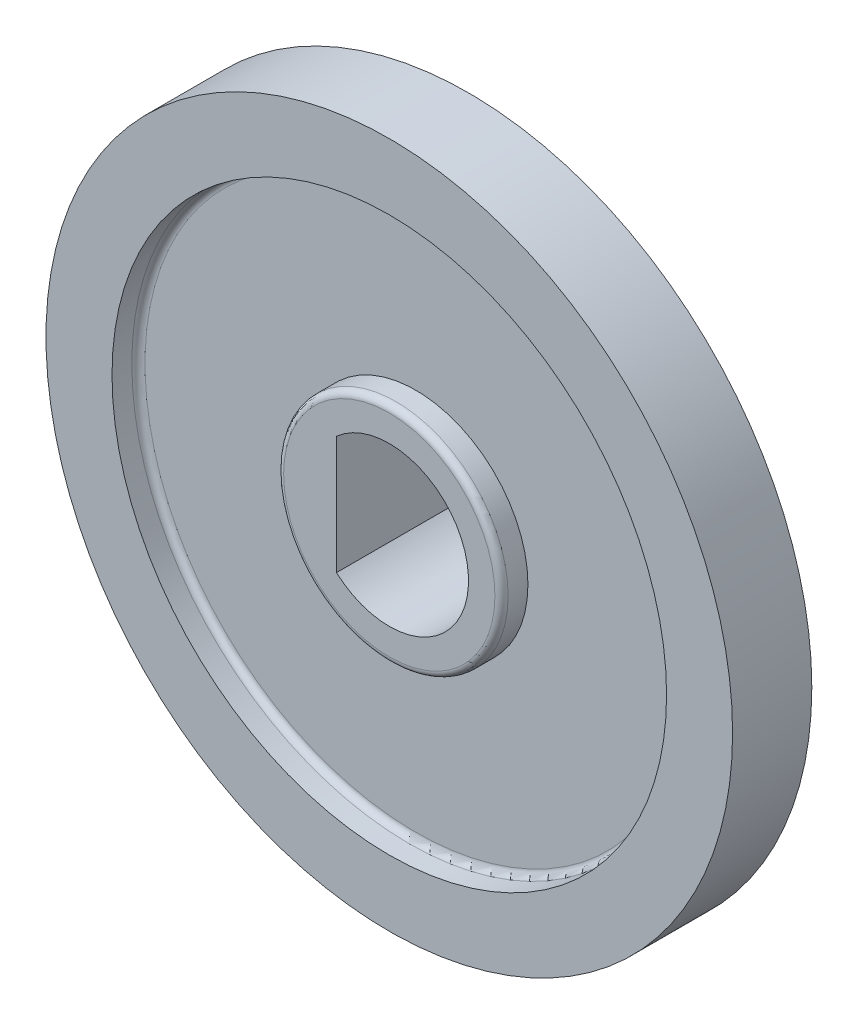
SolidWorks part; units mm, degrees
ref_plane "Plan de face" through (0, 0, 0) normal (0, 0, 1) x (1, 0, 0)
ref_plane "Plan de dessus" through (0, 0, 0) normal (0, 1, 0) x (1, 0, 0)
ref_plane "Plan de droite" through (0, 0, 0) normal (1, 0, 0) x (0, 0, -1)
sketch "Esquisse1" plane through (0, 0, 0) normal (0, 0, 1) x (1, 0, 0)
  line L0 (-2, 2.2361) -> (-2, -2.2361)
  arc A0 (12.9936, 0.4084) -> (12.9756, 0.7954) centre (0, 0) ccw
  arc A1 (12.8399, 2.0337) -> (12.7736, 2.4154) centre (0, 0) ccw
  arc A2 (12.4838, 3.6269) -> (12.3702, 3.9974) centre (0, 0) ccw
  arc A3 (11.9308, 5.1629) -> (11.7716, 5.5162) centre (0, 0) ccw
  arc A4 (11.1896, 6.6175) -> (10.9874, 6.9481) centre (0, 0) ccw
  arc A5 (10.272, 7.9678) -> (10.03, 8.2704) centre (0, 0) ccw
  arc A6 (9.1924, 9.1924) -> (8.9143, 9.4623) centre (0, 0) ccw
  arc A7 (7.9678, 10.272) -> (7.6581, 10.5049) centre (0, 0) ccw
  arc A8 (6.6175, 11.1897) -> (6.2811, 11.3819) centre (0, 0) ccw
  arc A9 (5.1629, 11.9308) -> (4.805, 12.0794) centre (0, 0) ccw
  arc A10 (3.6269, 12.4838) -> (3.2532, 12.5864) centre (0, 0) ccw
  arc A11 (2.0336, 12.84) -> (1.6501, 12.8949) centre (0, 0) ccw
  arc A12 (0.4083, 12.9936) -> (0.0209, 13) centre (0, 0) ccw
  arc A13 (-1.2234, 12.9423) -> (-1.6086, 12.9001) centre (0, 0) ccw
  arc A14 (-2.8359, 12.6869) -> (-3.2127, 12.5968) centre (0, 0) ccw
  arc A15 (-4.4036, 12.2314) -> (-4.7662, 12.0948) centre (0, 0) ccw
  arc A16 (-5.9019, 11.5831) -> (-6.2445, 11.402) centre (0, 0) ccw
  arc A17 (-7.3071, 10.752) -> (-7.6243, 10.5295) centre (0, 0) ccw
  arc A18 (-8.5971, 9.7514) -> (-8.8839, 9.4909) centre (0, 0) ccw
  arc A19 (-9.7515, 8.597) -> (-10.0033, 8.3026) centre (0, 0) ccw
  arc A20 (-10.7521, 7.3071) -> (-10.9651, 6.9834) centre (0, 0) ccw
  arc A21 (-11.5831, 5.9019) -> (-11.7538, 5.554) centre (0, 0) ccw
  arc A22 (-12.2315, 4.4036) -> (-12.3573, 4.0371) centre (0, 0) ccw
  arc A23 (-12.6869, 2.8358) -> (-12.7658, 2.4565) centre (0, 0) ccw
  arc A24 (-12.9423, 1.2234) -> (-12.973, 0.8371) centre (0, 0) ccw
  arc A25 (-12.9936, -0.4084) -> (-12.9756, -0.7954) centre (0, 0) ccw
  arc A26 (-12.8399, -2.0337) -> (-12.7736, -2.4154) centre (0, 0) ccw
  arc A27 (-12.4838, -3.6269) -> (-12.3702, -3.9974) centre (0, 0) ccw
  arc A28 (-11.9308, -5.1629) -> (-11.7716, -5.5162) centre (0, 0) ccw
  arc A29 (-11.1896, -6.6175) -> (-10.9874, -6.9481) centre (0, 0) ccw
  arc A30 (-10.272, -7.9678) -> (-10.03, -8.2704) centre (0, 0) ccw
  arc A31 (-9.1924, -9.1924) -> (-8.9143, -9.4623) centre (0, 0) ccw
  arc A32 (-7.9678, -10.272) -> (-7.6581, -10.5049) centre (0, 0) ccw
  arc A33 (-6.6175, -11.1897) -> (-6.2811, -11.3819) centre (0, 0) ccw
  arc A34 (-5.1629, -11.9308) -> (-4.805, -12.0794) centre (0, 0) ccw
  arc A35 (-3.6269, -12.4838) -> (-3.2532, -12.5864) centre (0, 0) ccw
  arc A36 (-2.0336, -12.84) -> (-1.6501, -12.8949) centre (0, 0) ccw
  arc A37 (-0.4083, -12.9936) -> (-0.0209, -13) centre (0, 0) ccw
  arc A38 (1.2234, -12.9423) -> (1.6086, -12.9001) centre (0, 0) ccw
  arc A39 (2.8359, -12.6869) -> (3.2127, -12.5968) centre (0, 0) ccw
  arc A40 (4.4036, -12.2314) -> (4.7662, -12.0948) centre (0, 0) ccw
  arc A41 (5.9019, -11.5831) -> (6.2445, -11.402) centre (0, 0) ccw
  arc A42 (7.3071, -10.752) -> (7.6243, -10.5295) centre (0, 0) ccw
  arc A43 (8.5971, -9.7514) -> (8.8839, -9.4909) centre (0, 0) ccw
  arc A44 (9.7515, -8.597) -> (10.0033, -8.3026) centre (0, 0) ccw
  arc A45 (10.7521, -7.3071) -> (10.9651, -6.9834) centre (0, 0) ccw
  arc A46 (11.5831, -5.9019) -> (11.7538, -5.554) centre (0, 0) ccw
  arc A47 (12.2315, -4.4036) -> (12.3573, -4.0371) centre (0, 0) ccw
  arc A48 (12.6869, -2.8358) -> (12.7658, -2.4565) centre (0, 0) ccw
  arc A49 (12.9423, -1.2234) -> (12.973, -0.8371) centre (0, 0) ccw
  arc A50 (11.8681, -0.4041) -> (11.875, 0.012) centre (0, 0) ccw
  arc A51 (11.8252, 1.0866) -> (11.7798, 1.5003) centre (0, 0) ccw
  arc A52 (11.5958, 2.5601) -> (11.4989, 2.9648) centre (0, 0) ccw
  arc A53 (11.1835, 3.9932) -> (11.0367, 4.3827) centre (0, 0) ccw
  arc A54 (10.5948, 5.3634) -> (10.4003, 5.7314) centre (0, 0) ccw
  arc A55 (9.839, 6.649) -> (9.6, 6.9897) centre (0, 0) ccw
  arc A56 (8.9281, 7.8297) -> (8.6483, 8.1378) centre (0, 0) ccw
  arc A57 (7.8764, 8.887) -> (7.5601, 9.1575) centre (0, 0) ccw
  arc A58 (6.7004, 9.8041) -> (6.3528, 10.0328) centre (0, 0) ccw
  arc A59 (5.4188, 10.5666) -> (5.0452, 10.7499) centre (0, 0) ccw
  arc A60 (4.0518, 11.1624) -> (3.6581, 11.2975) centre (0, 0) ccw
  arc A61 (2.6208, 11.5822) -> (2.2133, 11.6669) centre (0, 0) ccw
  arc A62 (1.1485, 11.8193) -> (0.7336, 11.8523) centre (0, 0) ccw
  arc A63 (-0.3419, 11.8701) -> (-0.7576, 11.8508) centre (0, 0) ccw
  arc A64 (-1.8269, 11.7336) -> (-2.237, 11.6624) centre (0, 0) ccw
  arc A65 (-3.2831, 11.4121) -> (-3.681, 11.2901) centre (0, 0) ccw
  arc A66 (-4.6876, 10.9106) -> (-5.067, 10.7397) centre (0, 0) ccw
  arc A67 (-6.0181, 10.2371) -> (-6.3731, 10.0199) centre (0, 0) ccw
  arc A68 (-7.2537, 9.4021) -> (-7.5787, 9.1422) centre (0, 0) ccw
  arc A69 (-8.3749, 8.4189) -> (-8.6647, 8.1202) centre (0, 0) ccw
  arc A70 (-9.364, 7.3028) -> (-9.6141, 6.9702) centre (0, 0) ccw
  arc A71 (-10.2054, 6.0716) -> (-10.4119, 5.7103) centre (0, 0) ccw
  arc A72 (-10.886, 4.7447) -> (-11.0455, 4.3603) centre (0, 0) ccw
  arc A73 (-11.3948, 3.3429) -> (-11.5049, 2.9415) centre (0, 0) ccw
  arc A74 (-11.7239, 1.8884) -> (-11.7829, 1.4764) centre (0, 0) ccw
  arc A75 (-11.8681, 0.4041) -> (-11.875, -0.012) centre (0, 0) ccw
  arc A76 (-11.8252, -1.0866) -> (-11.7798, -1.5003) centre (0, 0) ccw
  arc A77 (-11.5958, -2.5601) -> (-11.4989, -2.9648) centre (0, 0) ccw
  arc A78 (-11.1835, -3.9932) -> (-11.0367, -4.3827) centre (0, 0) ccw
  arc A79 (-10.5948, -5.3634) -> (-10.4003, -5.7314) centre (0, 0) ccw
  arc A80 (-9.839, -6.649) -> (-9.6, -6.9897) centre (0, 0) ccw
  arc A81 (-8.9281, -7.8297) -> (-8.6483, -8.1378) centre (0, 0) ccw
  arc A82 (-7.8764, -8.887) -> (-7.5601, -9.1575) centre (0, 0) ccw
  arc A83 (-6.7004, -9.8041) -> (-6.3528, -10.0328) centre (0, 0) ccw
  arc A84 (-5.4188, -10.5666) -> (-5.0452, -10.7499) centre (0, 0) ccw
  arc A85 (-4.0518, -11.1624) -> (-3.6581, -11.2975) centre (0, 0) ccw
  arc A86 (-2.6208, -11.5822) -> (-2.2133, -11.6669) centre (0, 0) ccw
  arc A87 (-1.1485, -11.8193) -> (-0.7336, -11.8523) centre (0, 0) ccw
  arc A88 (0.3419, -11.8701) -> (0.7576, -11.8508) centre (0, 0) ccw
  arc A89 (1.8269, -11.7336) -> (2.237, -11.6624) centre (0, 0) ccw
  arc A90 (3.2831, -11.4121) -> (3.681, -11.2901) centre (0, 0) ccw
  arc A91 (4.6876, -10.9106) -> (5.067, -10.7397) centre (0, 0) ccw
  arc A92 (6.0181, -10.2371) -> (6.3731, -10.0199) centre (0, 0) ccw
  arc A93 (7.2537, -9.4021) -> (7.5787, -9.1422) centre (0, 0) ccw
  arc A94 (8.3749, -8.4189) -> (8.6647, -8.1202) centre (0, 0) ccw
  arc A95 (9.364, -7.3028) -> (9.6141, -6.9702) centre (0, 0) ccw
  arc A96 (10.2054, -6.0716) -> (10.4119, -5.7103) centre (0, 0) ccw
  arc A97 (10.886, -4.7447) -> (11.0455, -4.3603) centre (0, 0) ccw
  arc A98 (11.3948, -3.3429) -> (11.5049, -2.9415) centre (0, 0) ccw
  arc A99 (11.7239, -1.8884) -> (11.7829, -1.4764) centre (0, 0) ccw
  arc A100 (-2, -2.2361) -> (-2, 2.2361) centre (0, 0) ccw
  spline S0 degree 3 poles (11.875, 0.012) (11.8924, 0.0149) (12.1056, 0.0543) (12.4729, 0.1636) (12.819, 0.3195) (12.9805, 0.4016) (12.9936, 0.4084) knots 0.129628 0.129628 0.129628 0.129628 0.182246 0.777177 1.275527 1.319645 1.319645 1.319645 1.319645
  spline S1 degree 3 poles (11.8252, 1.0866) (11.8427, 1.0853) (12.0587, 1.0658) (12.4346, 0.991) (12.7936, 0.8677) (12.962, 0.8009) (12.9756, 0.7954) knots 0.129628 0.129628 0.129628 0.129628 0.182246 0.777177 1.275527 1.319645 1.319645 1.319645 1.319645
  spline S2 degree 3 poles (11.7798, 1.5003) (11.7967, 1.5053) (12.0034, 1.5711) (12.3541, 1.7256) (12.6778, 1.9236) (12.8278, 2.0253) (12.8399, 2.0337) knots 0.129628 0.129628 0.129628 0.129628 0.182246 0.777177 1.275527 1.319645 1.319645 1.319645 1.319645
  spline S3 degree 3 poles (11.5958, 2.5601) (11.6133, 2.5611) (11.8301, 2.5688) (12.2123, 2.5416) (12.5839, 2.4644) (12.7594, 2.4192) (12.7736, 2.4154) knots 0.129628 0.129628 0.129628 0.129628 0.182246 0.777177 1.275527 1.319645 1.319645 1.319645 1.319645
  spline S4 degree 3 poles (11.4989, 2.9648) (11.515, 2.9719) (11.7118, 3.0631) (12.0404, 3.2603) (12.3368, 3.4974) (12.4728, 3.6171) (12.4838, 3.6269) knots 0.129628 0.129628 0.129628 0.129628 0.182246 0.777177 1.275527 1.319645 1.319645 1.319645 1.319645
  spline S5 degree 3 poles (11.1835, 3.9932) (11.2008, 3.9964) (11.4148, 4.0312) (11.7975, 4.0522) (12.1758, 4.0221) (12.3556, 3.9993) (12.3702, 3.9974) knots 0.129628 0.129628 0.129628 0.129628 0.182246 0.777177 1.275527 1.319645 1.319645 1.319645 1.319645
  spline S6 degree 3 poles (11.0367, 4.3827) (11.0518, 4.3917) (11.2355, 4.5069) (11.5368, 4.7437) (11.8012, 5.0161) (11.9211, 5.1519) (11.9308, 5.1629) knots 0.129628 0.129628 0.129628 0.129628 0.182246 0.777177 1.275527 1.319645 1.319645 1.319645 1.319645
  spline S7 degree 3 poles (10.5948, 5.3634) (10.6116, 5.3687) (10.8196, 5.4301) (11.1966, 5.4989) (11.5757, 5.5164) (11.7569, 5.5163) (11.7716, 5.5162) knots 0.129628 0.129628 0.129628 0.129628 0.182246 0.777177 1.275527 1.319645 1.319645 1.319645 1.319645
  spline S8 degree 3 poles (10.4003, 5.7314) (10.4142, 5.7422) (10.5821, 5.8795) (10.8513, 6.1522) (11.0794, 6.4556) (11.1814, 6.6053) (11.1896, 6.6175) knots 0.129628 0.129628 0.129628 0.129628 0.182246 0.777177 1.275527 1.319645 1.319645 1.319645 1.319645
  spline S9 degree 3 poles (9.839, 6.649) (9.855, 6.6564) (10.0537, 6.7433) (10.4191, 6.8588) (10.793, 6.9238) (10.9728, 6.9463) (10.9874, 6.9481) knots 0.129628 0.129628 0.129628 0.129628 0.182246 0.777177 1.275527 1.319645 1.319645 1.319645 1.319645
  spline S10 degree 3 poles (9.6, 6.9897) (9.6124, 7.0022) (9.7617, 7.1594) (9.9947, 7.4638) (10.183, 7.7933) (10.2654, 7.9547) (10.272, 7.9678) knots 0.129628 0.129628 0.129628 0.129628 0.182246 0.777177 1.275527 1.319645 1.319645 1.319645 1.319645
  spline S11 degree 3 poles (8.9281, 7.8297) (8.943, 7.839) (9.1293, 7.9502) (9.4773, 8.1106) (9.8402, 8.2219) (10.0157, 8.2668) (10.03, 8.2704) knots 0.129628 0.129628 0.129628 0.129628 0.182246 0.777177 1.275527 1.319645 1.319645 1.319645 1.319645
  spline S12 degree 3 poles (8.6483, 8.1378) (8.659, 8.1517) (8.7874, 8.3265) (8.9804, 8.6576) (9.1259, 9.0081) (9.1874, 9.1785) (9.1924, 9.1924) knots 0.129628 0.129628 0.129628 0.129628 0.182246 0.777177 1.275527 1.319645 1.319645 1.319645 1.319645
  spline S13 degree 3 poles (7.8764, 8.887) (7.89, 8.8981) (8.0608, 9.0317) (8.386, 9.2344) (8.7321, 9.3904) (8.9006, 9.4569) (8.9143, 9.4623) knots 0.129628 0.129628 0.129628 0.129628 0.182246 0.777177 1.275527 1.319645 1.319645 1.319645 1.319645
  spline S14 degree 3 poles (7.5601, 9.1575) (7.569, 9.1727) (7.6746, 9.3622) (7.8245, 9.7148) (7.9249, 10.0809) (7.9646, 10.2576) (7.9678, 10.272) knots 0.129628 0.129628 0.129628 0.129628 0.182246 0.777177 1.275527 1.319645 1.319645 1.319645 1.319645
  spline S15 degree 3 poles (6.7004, 9.8041) (6.7126, 9.8168) (6.8653, 9.9708) (7.1625, 10.2127) (7.4863, 10.4107) (7.6451, 10.4979) (7.6581, 10.5049) knots 0.129628 0.129628 0.129628 0.129628 0.182246 0.777177 1.275527 1.319645 1.319645 1.319645 1.319645
  spline S16 degree 3 poles (6.3528, 10.0328) (6.3597, 10.049) (6.4407, 10.2502) (6.5452, 10.6189) (6.599, 10.9946) (6.6162, 11.175) (6.6175, 11.1897) knots 0.129628 0.129628 0.129628 0.129628 0.182246 0.777177 1.275527 1.319645 1.319645 1.319645 1.319645
  spline S17 degree 3 poles (5.4188, 10.5666) (5.4293, 10.5807) (5.5615, 10.7526) (5.8261, 11.0299) (6.1225, 11.2669) (6.2691, 11.3733) (6.2811, 11.3819) knots 0.129628 0.129628 0.129628 0.129628 0.182246 0.777177 1.275527 1.319645 1.319645 1.319645 1.319645
  spline S18 degree 3 poles (5.0452, 10.7499) (5.0501, 10.7669) (5.1052, 10.9766) (5.1627, 11.3555) (5.169, 11.735) (5.1634, 11.9161) (5.1629, 11.9308) knots 0.129628 0.129628 0.129628 0.129628 0.182246 0.777177 1.275527 1.319645 1.319645 1.319645 1.319645
  spline S19 degree 3 poles (4.0518, 11.1624) (4.0604, 11.1777) (4.17, 11.3649) (4.3977, 11.6731) (4.6621, 11.9454) (4.7942, 12.0694) (4.805, 12.0794) knots 0.129628 0.129628 0.129628 0.129628 0.182246 0.777177 1.275527 1.319645 1.319645 1.319645 1.319645
  spline S20 degree 3 poles (3.6581, 11.2975) (3.6608, 11.3149) (3.6892, 11.5299) (3.6988, 11.913) (3.6574, 12.2903) (3.6292, 12.4693) (3.6269, 12.4838) knots 0.129628 0.129628 0.129628 0.129628 0.182246 0.777177 1.275527 1.319645 1.319645 1.319645 1.319645
  spline S21 degree 3 poles (2.6208, 11.5822) (2.6274, 11.5985) (2.7127, 11.7979) (2.9, 12.1322) (3.1282, 12.4355) (3.2437, 12.5751) (3.2532, 12.5864) knots 0.129628 0.129628 0.129628 0.129628 0.182246 0.777177 1.275527 1.319645 1.319645 1.319645 1.319645
  spline S22 degree 3 poles (2.2133, 11.6669) (2.2138, 11.6845) (2.215, 11.9014) (2.1765, 12.2827) (2.0882, 12.6518) (2.0378, 12.8258) (2.0336, 12.84) knots 0.129628 0.129628 0.129628 0.129628 0.182246 0.777177 1.275527 1.319645 1.319645 1.319645 1.319645
  spline S23 degree 3 poles (1.1485, 11.8193) (1.153, 11.8363) (1.2126, 12.0449) (1.3566, 12.4) (1.5449, 12.7295) (1.6421, 12.8824) (1.6501, 12.8949) knots 0.129628 0.129628 0.129628 0.129628 0.182246 0.777177 1.275527 1.319645 1.319645 1.319645 1.319645
  spline S24 degree 3 poles (0.7336, 11.8523) (0.7319, 11.8698) (0.7059, 12.0851) (0.6199, 12.4586) (0.486, 12.8137) (0.4142, 12.9801) (0.4083, 12.9936) knots 0.129628 0.129628 0.129628 0.129628 0.182246 0.777177 1.275527 1.319645 1.319645 1.319645 1.319645
  spline S25 degree 3 poles (-0.3419, 11.8701) (-0.3396, 11.8875) (-0.3065, 12.1019) (-0.2082, 12.4723) (-0.0627, 12.8228) (0.0146, 12.9867) (0.0209, 13) knots 0.129628 0.129628 0.129628 0.129628 0.182246 0.777177 1.275527 1.319645 1.319645 1.319645 1.319645
  spline S26 degree 3 poles (-0.7576, 11.8508) (-0.7616, 11.868) (-0.8143, 12.0783) (-0.9465, 12.438) (-1.1238, 12.7736) (-1.2159, 12.9296) (-1.2234, 12.9423) knots 0.129628 0.129628 0.129628 0.129628 0.182246 0.777177 1.275527 1.319645 1.319645 1.319645 1.319645
  spline S27 degree 3 poles (-1.8269, 11.7336) (-1.8268, 11.7512) (-1.8209, 11.968) (-1.7698, 12.3478) (-1.6693, 12.7138) (-1.6132, 12.8861) (-1.6086, 12.9001) knots 0.129628 0.129628 0.129628 0.129628 0.182246 0.777177 1.275527 1.319645 1.319645 1.319645 1.319645
  spline S28 degree 3 poles (-2.237, 11.6624) (-2.243, 11.6789) (-2.3217, 11.881) (-2.4979, 12.2213) (-2.7159, 12.532) (-2.8268, 12.6753) (-2.8359, 12.6869) knots 0.129628 0.129628 0.129628 0.129628 0.182246 0.777177 1.275527 1.319645 1.319645 1.319645 1.319645
  spline S29 degree 3 poles (-3.2831, 11.4121) (-3.2852, 11.4296) (-3.3065, 11.6454) (-3.3034, 12.0286) (-3.2496, 12.4044) (-3.2156, 12.5823) (-3.2127, 12.5968) knots 0.129628 0.129628 0.129628 0.129628 0.182246 0.777177 1.275527 1.319645 1.319645 1.319645 1.319645
  spline S30 degree 3 poles (-3.681, 11.2901) (-3.6891, 11.3057) (-3.7925, 11.4963) (-4.0099, 11.8119) (-4.2652, 12.0928) (-4.3932, 12.2211) (-4.4036, 12.2314) knots 0.129628 0.129628 0.129628 0.129628 0.182246 0.777177 1.275527 1.319645 1.319645 1.319645 1.319645
  spline S31 degree 3 poles (-4.6876, 10.9106) (-4.6918, 10.9277) (-4.74, 11.1392) (-4.785, 11.5198) (-4.7787, 11.8993) (-4.7672, 12.0801) (-4.7662, 12.0948) knots 0.129628 0.129628 0.129628 0.129628 0.182246 0.777177 1.275527 1.319645 1.319645 1.319645 1.319645
  spline S32 degree 3 poles (-5.067, 10.7397) (-5.077, 10.7542) (-5.2035, 10.9304) (-5.4587, 11.2162) (-5.7472, 11.4629) (-5.8902, 11.5741) (-5.9019, 11.5831) knots 0.129628 0.129628 0.129628 0.129628 0.182246 0.777177 1.275527 1.319645 1.319645 1.319645 1.319645
  spline S33 degree 3 poles (-6.0181, 10.2371) (-6.0244, 10.2535) (-6.0987, 10.4573) (-6.191, 10.8292) (-6.2324, 11.2065) (-6.2436, 11.3873) (-6.2445, 11.402) knots 0.129628 0.129628 0.129628 0.129628 0.182246 0.777177 1.275527 1.319645 1.319645 1.319645 1.319645
  spline S34 degree 3 poles (-6.3731, 10.0199) (-6.3848, 10.0331) (-6.5324, 10.192) (-6.8215, 10.4436) (-7.1385, 10.6522) (-7.2944, 10.7446) (-7.3071, 10.752) knots 0.129628 0.129628 0.129628 0.129628 0.182246 0.777177 1.275527 1.319645 1.319645 1.319645 1.319645
  spline S35 degree 3 poles (-7.2537, 9.4021) (-7.262, 9.4176) (-7.3613, 9.6104) (-7.4995, 9.9679) (-7.5878, 10.337) (-7.6216, 10.515) (-7.6243, 10.5295) knots 0.129628 0.129628 0.129628 0.129628 0.182246 0.777177 1.275527 1.319645 1.319645 1.319645 1.319645
  spline S36 degree 3 poles (-7.5787, 9.1422) (-7.5919, 9.1537) (-7.7583, 9.2929) (-8.0766, 9.5063) (-8.4173, 9.6735) (-8.5835, 9.7456) (-8.5971, 9.7514) knots 0.129628 0.129628 0.129628 0.129628 0.182246 0.777177 1.275527 1.319645 1.319645 1.319645 1.319645
  spline S37 degree 3 poles (-8.3749, 8.4189) (-8.3851, 8.4332) (-8.5077, 8.612) (-8.6897, 8.9493) (-8.8235, 9.3045) (-8.8794, 9.4768) (-8.8839, 9.4909) knots 0.129628 0.129628 0.129628 0.129628 0.182246 0.777177 1.275527 1.319645 1.319645 1.319645 1.319645
  spline S38 degree 3 poles (-8.6647, 8.1202) (-8.6793, 8.13) (-8.8618, 8.2473) (-9.2044, 8.4191) (-9.5633, 8.5423) (-9.7373, 8.593) (-9.7515, 8.597) knots 0.129628 0.129628 0.129628 0.129628 0.182246 0.777177 1.275527 1.319645 1.319645 1.319645 1.319645
  spline S39 degree 3 poles (-9.364, 7.3028) (-9.3759, 7.3157) (-9.52, 7.4778) (-9.7428, 7.7897) (-9.9201, 8.1252) (-9.9971, 8.2892) (-10.0033, 8.3026) knots 0.129628 0.129628 0.129628 0.129628 0.182246 0.777177 1.275527 1.319645 1.319645 1.319645 1.319645
  spline S40 degree 3 poles (-9.6141, 6.9702) (-9.6299, 6.9781) (-9.8256, 7.0716) (-10.187, 7.1991) (-10.5586, 7.2763) (-10.7375, 7.3048) (-10.7521, 7.3071) knots 0.129628 0.129628 0.129628 0.129628 0.182246 0.777177 1.275527 1.319645 1.319645 1.319645 1.319645
  spline S41 degree 3 poles (-10.2054, 6.0716) (-10.2189, 6.0829) (-10.3822, 6.2257) (-10.6423, 6.5071) (-10.8603, 6.8179) (-10.9572, 6.9709) (-10.9651, 6.9834) knots 0.129628 0.129628 0.129628 0.129628 0.182246 0.777177 1.275527 1.319645 1.319645 1.319645 1.319645
  spline S42 degree 3 poles (-10.4119, 5.7103) (-10.4285, 5.7161) (-10.6344, 5.7843) (-11.0089, 5.8655) (-11.3873, 5.8956) (-11.5684, 5.9014) (-11.5831, 5.9019) knots 0.129628 0.129628 0.129628 0.129628 0.182246 0.777177 1.275527 1.319645 1.319645 1.319645 1.319645
  spline S43 degree 3 poles (-10.886, 4.7447) (-10.9007, 4.7542) (-11.0806, 4.8754) (-11.3739, 5.122) (-11.6291, 5.4029) (-11.7445, 5.5426) (-11.7538, 5.554) knots 0.129628 0.129628 0.129628 0.129628 0.182246 0.777177 1.275527 1.319645 1.319645 1.319645 1.319645
  spline S44 degree 3 poles (-11.0455, 4.3603) (-11.0627, 4.364) (-11.2755, 4.4059) (-11.6573, 4.4395) (-12.0364, 4.4219) (-12.2168, 4.405) (-12.2315, 4.4036) knots 0.129628 0.129628 0.129628 0.129628 0.182246 0.777177 1.275527 1.319645 1.319645 1.319645 1.319645
  spline S45 degree 3 poles (-11.3948, 3.3429) (-11.4106, 3.3505) (-11.6043, 3.4481) (-11.9262, 3.6561) (-12.2146, 3.9028) (-12.3466, 4.0269) (-12.3573, 4.0371) knots 0.129628 0.129628 0.129628 0.129628 0.182246 0.777177 1.275527 1.319645 1.319645 1.319645 1.319645
  spline S46 degree 3 poles (-11.5049, 2.9415) (-11.5224, 2.9431) (-11.7388, 2.9579) (-12.1218, 2.9434) (-12.4957, 2.8785) (-12.6725, 2.8391) (-12.6869, 2.8358) knots 0.129628 0.129628 0.129628 0.129628 0.182246 0.777177 1.275527 1.319645 1.319645 1.319645 1.319645
  spline S47 degree 3 poles (-11.7239, 1.8884) (-11.7406, 1.8939) (-11.9449, 1.9666) (-12.2904, 2.1325) (-12.6074, 2.3412) (-12.7539, 2.4478) (-12.7658, 2.4565) knots 0.129628 0.129628 0.129628 0.129628 0.182246 0.777177 1.275527 1.319645 1.319645 1.319645 1.319645
  spline S48 degree 3 poles (-11.7829, 1.4764) (-11.8005, 1.4757) (-12.017, 1.4634) (-12.3951, 1.401) (-12.7579, 1.2897) (-12.9285, 1.2284) (-12.9423, 1.2234) knots 0.129628 0.129628 0.129628 0.129628 0.182246 0.777177 1.275527 1.319645 1.319645 1.319645 1.319645
  spline S49 degree 3 poles (-11.8681, 0.4041) (-11.8854, 0.4075) (-12.0972, 0.454) (-12.4607, 0.5753) (-12.8014, 0.7426) (-12.9601, 0.83) (-12.973, 0.8371) knots 0.129628 0.129628 0.129628 0.129628 0.182246 0.777177 1.275527 1.319645 1.319645 1.319645 1.319645
  spline S50 degree 3 poles (-11.875, -0.012) (-11.8924, -0.0149) (-12.1056, -0.0543) (-12.4729, -0.1636) (-12.819, -0.3195) (-12.9805, -0.4016) (-12.9936, -0.4084) knots 0.129628 0.129628 0.129628 0.129628 0.182246 0.777177 1.275527 1.319645 1.319645 1.319645 1.319645
  spline S51 degree 3 poles (-11.8252, -1.0866) (-11.8427, -1.0853) (-12.0587, -1.0658) (-12.4346, -0.991) (-12.7936, -0.8677) (-12.962, -0.8009) (-12.9756, -0.7954) knots 0.129628 0.129628 0.129628 0.129628 0.182246 0.777177 1.275527 1.319645 1.319645 1.319645 1.319645
  spline S52 degree 3 poles (-11.7798, -1.5003) (-11.7967, -1.5053) (-12.0034, -1.5711) (-12.3541, -1.7256) (-12.6778, -1.9236) (-12.8278, -2.0253) (-12.8399, -2.0337) knots 0.129628 0.129628 0.129628 0.129628 0.182246 0.777177 1.275527 1.319645 1.319645 1.319645 1.319645
  spline S53 degree 3 poles (-11.5958, -2.5601) (-11.6133, -2.5611) (-11.8301, -2.5688) (-12.2123, -2.5416) (-12.5839, -2.4644) (-12.7594, -2.4192) (-12.7736, -2.4154) knots 0.129628 0.129628 0.129628 0.129628 0.182246 0.777177 1.275527 1.319645 1.319645 1.319645 1.319645
  spline S54 degree 3 poles (-11.4989, -2.9648) (-11.515, -2.9719) (-11.7118, -3.0631) (-12.0404, -3.2603) (-12.3368, -3.4974) (-12.4728, -3.6171) (-12.4838, -3.6269) knots 0.129628 0.129628 0.129628 0.129628 0.182246 0.777177 1.275527 1.319645 1.319645 1.319645 1.319645
  spline S55 degree 3 poles (-11.1835, -3.9932) (-11.2008, -3.9964) (-11.4148, -4.0312) (-11.7975, -4.0522) (-12.1758, -4.0221) (-12.3556, -3.9993) (-12.3702, -3.9974) knots 0.129628 0.129628 0.129628 0.129628 0.182246 0.777177 1.275527 1.319645 1.319645 1.319645 1.319645
  spline S56 degree 3 poles (-11.0367, -4.3827) (-11.0518, -4.3917) (-11.2355, -4.5069) (-11.5368, -4.7437) (-11.8012, -5.0161) (-11.9211, -5.1519) (-11.9308, -5.1629) knots 0.129628 0.129628 0.129628 0.129628 0.182246 0.777177 1.275527 1.319645 1.319645 1.319645 1.319645
  spline S57 degree 3 poles (-10.5948, -5.3634) (-10.6116, -5.3687) (-10.8196, -5.4301) (-11.1966, -5.4989) (-11.5757, -5.5164) (-11.7569, -5.5163) (-11.7716, -5.5162) knots 0.129628 0.129628 0.129628 0.129628 0.182246 0.777177 1.275527 1.319645 1.319645 1.319645 1.319645
  spline S58 degree 3 poles (-10.4003, -5.7314) (-10.4142, -5.7422) (-10.5821, -5.8795) (-10.8513, -6.1522) (-11.0794, -6.4556) (-11.1814, -6.6053) (-11.1896, -6.6175) knots 0.129628 0.129628 0.129628 0.129628 0.182246 0.777177 1.275527 1.319645 1.319645 1.319645 1.319645
  spline S59 degree 3 poles (-9.839, -6.649) (-9.855, -6.6564) (-10.0537, -6.7433) (-10.4191, -6.8588) (-10.793, -6.9238) (-10.9728, -6.9463) (-10.9874, -6.9481) knots 0.129628 0.129628 0.129628 0.129628 0.182246 0.777177 1.275527 1.319645 1.319645 1.319645 1.319645
  spline S60 degree 3 poles (-9.6, -6.9897) (-9.6124, -7.0022) (-9.7617, -7.1594) (-9.9947, -7.4638) (-10.183, -7.7933) (-10.2654, -7.9547) (-10.272, -7.9678) knots 0.129628 0.129628 0.129628 0.129628 0.182246 0.777177 1.275527 1.319645 1.319645 1.319645 1.319645
  spline S61 degree 3 poles (-8.9281, -7.8297) (-8.943, -7.839) (-9.1293, -7.9502) (-9.4773, -8.1106) (-9.8402, -8.2219) (-10.0157, -8.2668) (-10.03, -8.2704) knots 0.129628 0.129628 0.129628 0.129628 0.182246 0.777177 1.275527 1.319645 1.319645 1.319645 1.319645
  spline S62 degree 3 poles (-8.6483, -8.1378) (-8.659, -8.1517) (-8.7874, -8.3265) (-8.9804, -8.6576) (-9.1259, -9.0081) (-9.1874, -9.1785) (-9.1924, -9.1924) knots 0.129628 0.129628 0.129628 0.129628 0.182246 0.777177 1.275527 1.319645 1.319645 1.319645 1.319645
  spline S63 degree 3 poles (-7.8764, -8.887) (-7.89, -8.8981) (-8.0608, -9.0317) (-8.386, -9.2344) (-8.7321, -9.3904) (-8.9006, -9.4569) (-8.9143, -9.4623) knots 0.129628 0.129628 0.129628 0.129628 0.182246 0.777177 1.275527 1.319645 1.319645 1.319645 1.319645
  spline S64 degree 3 poles (-7.5601, -9.1575) (-7.569, -9.1727) (-7.6746, -9.3622) (-7.8245, -9.7148) (-7.9249, -10.0809) (-7.9646, -10.2576) (-7.9678, -10.272) knots 0.129628 0.129628 0.129628 0.129628 0.182246 0.777177 1.275527 1.319645 1.319645 1.319645 1.319645
  spline S65 degree 3 poles (-6.7004, -9.8041) (-6.7126, -9.8168) (-6.8653, -9.9708) (-7.1625, -10.2127) (-7.4863, -10.4107) (-7.6451, -10.4979) (-7.6581, -10.5049) knots 0.129628 0.129628 0.129628 0.129628 0.182246 0.777177 1.275527 1.319645 1.319645 1.319645 1.319645
  spline S66 degree 3 poles (-6.3528, -10.0328) (-6.3597, -10.049) (-6.4407, -10.2502) (-6.5452, -10.6189) (-6.599, -10.9946) (-6.6162, -11.175) (-6.6175, -11.1897) knots 0.129628 0.129628 0.129628 0.129628 0.182246 0.777177 1.275527 1.319645 1.319645 1.319645 1.319645
  spline S67 degree 3 poles (-5.4188, -10.5666) (-5.4293, -10.5807) (-5.5615, -10.7526) (-5.8261, -11.0299) (-6.1225, -11.2669) (-6.2691, -11.3733) (-6.2811, -11.3819) knots 0.129628 0.129628 0.129628 0.129628 0.182246 0.777177 1.275527 1.319645 1.319645 1.319645 1.319645
  spline S68 degree 3 poles (-5.0452, -10.7499) (-5.0501, -10.7669) (-5.1052, -10.9766) (-5.1627, -11.3555) (-5.169, -11.735) (-5.1634, -11.9161) (-5.1629, -11.9308) knots 0.129628 0.129628 0.129628 0.129628 0.182246 0.777177 1.275527 1.319645 1.319645 1.319645 1.319645
  spline S69 degree 3 poles (-4.0518, -11.1624) (-4.0604, -11.1777) (-4.17, -11.3649) (-4.3977, -11.6731) (-4.6621, -11.9454) (-4.7942, -12.0694) (-4.805, -12.0794) knots 0.129628 0.129628 0.129628 0.129628 0.182246 0.777177 1.275527 1.319645 1.319645 1.319645 1.319645
  spline S70 degree 3 poles (-3.6581, -11.2975) (-3.6608, -11.3149) (-3.6892, -11.5299) (-3.6988, -11.913) (-3.6574, -12.2903) (-3.6292, -12.4693) (-3.6269, -12.4838) knots 0.129628 0.129628 0.129628 0.129628 0.182246 0.777177 1.275527 1.319645 1.319645 1.319645 1.319645
  spline S71 degree 3 poles (-2.6208, -11.5822) (-2.6274, -11.5985) (-2.7127, -11.7979) (-2.9, -12.1322) (-3.1282, -12.4355) (-3.2437, -12.5751) (-3.2532, -12.5864) knots 0.129628 0.129628 0.129628 0.129628 0.182246 0.777177 1.275527 1.319645 1.319645 1.319645 1.319645
  spline S72 degree 3 poles (-2.2133, -11.6669) (-2.2138, -11.6845) (-2.215, -11.9014) (-2.1765, -12.2827) (-2.0882, -12.6518) (-2.0378, -12.8258) (-2.0336, -12.84) knots 0.129628 0.129628 0.129628 0.129628 0.182246 0.777177 1.275527 1.319645 1.319645 1.319645 1.319645
  spline S73 degree 3 poles (-1.1485, -11.8193) (-1.153, -11.8363) (-1.2126, -12.0449) (-1.3566, -12.4) (-1.5449, -12.7295) (-1.6421, -12.8824) (-1.6501, -12.8949) knots 0.129628 0.129628 0.129628 0.129628 0.182246 0.777177 1.275527 1.319645 1.319645 1.319645 1.319645
  spline S74 degree 3 poles (-0.7336, -11.8523) (-0.7319, -11.8698) (-0.7059, -12.0851) (-0.6199, -12.4586) (-0.486, -12.8137) (-0.4142, -12.9801) (-0.4083, -12.9936) knots 0.129628 0.129628 0.129628 0.129628 0.182246 0.777177 1.275527 1.319645 1.319645 1.319645 1.319645
  spline S75 degree 3 poles (0.3419, -11.8701) (0.3396, -11.8875) (0.3065, -12.1019) (0.2082, -12.4723) (0.0627, -12.8228) (-0.0146, -12.9867) (-0.0209, -13) knots 0.129628 0.129628 0.129628 0.129628 0.182246 0.777177 1.275527 1.319645 1.319645 1.319645 1.319645
  spline S76 degree 3 poles (0.7576, -11.8508) (0.7616, -11.868) (0.8143, -12.0783) (0.9465, -12.438) (1.1238, -12.7736) (1.2159, -12.9296) (1.2234, -12.9423) knots 0.129628 0.129628 0.129628 0.129628 0.182246 0.777177 1.275527 1.319645 1.319645 1.319645 1.319645
  spline S77 degree 3 poles (1.8269, -11.7336) (1.8268, -11.7512) (1.8209, -11.968) (1.7698, -12.3478) (1.6693, -12.7138) (1.6132, -12.8861) (1.6086, -12.9001) knots 0.129628 0.129628 0.129628 0.129628 0.182246 0.777177 1.275527 1.319645 1.319645 1.319645 1.319645
  spline S78 degree 3 poles (2.237, -11.6624) (2.243, -11.6789) (2.3217, -11.881) (2.4979, -12.2213) (2.7159, -12.532) (2.8268, -12.6753) (2.8359, -12.6869) knots 0.129628 0.129628 0.129628 0.129628 0.182246 0.777177 1.275527 1.319645 1.319645 1.319645 1.319645
  spline S79 degree 3 poles (3.2831, -11.4121) (3.2852, -11.4296) (3.3065, -11.6454) (3.3034, -12.0286) (3.2496, -12.4044) (3.2156, -12.5823) (3.2127, -12.5968) knots 0.129628 0.129628 0.129628 0.129628 0.182246 0.777177 1.275527 1.319645 1.319645 1.319645 1.319645
  spline S80 degree 3 poles (3.681, -11.2901) (3.6891, -11.3057) (3.7925, -11.4963) (4.0099, -11.8119) (4.2652, -12.0928) (4.3932, -12.2211) (4.4036, -12.2314) knots 0.129628 0.129628 0.129628 0.129628 0.182246 0.777177 1.275527 1.319645 1.319645 1.319645 1.319645
  spline S81 degree 3 poles (4.6876, -10.9106) (4.6918, -10.9277) (4.74, -11.1392) (4.785, -11.5198) (4.7787, -11.8993) (4.7672, -12.0801) (4.7662, -12.0948) knots 0.129628 0.129628 0.129628 0.129628 0.182246 0.777177 1.275527 1.319645 1.319645 1.319645 1.319645
  spline S82 degree 3 poles (5.067, -10.7397) (5.077, -10.7542) (5.2035, -10.9304) (5.4587, -11.2162) (5.7472, -11.4629) (5.8902, -11.5741) (5.9019, -11.5831) knots 0.129628 0.129628 0.129628 0.129628 0.182246 0.777177 1.275527 1.319645 1.319645 1.319645 1.319645
  spline S83 degree 3 poles (6.0181, -10.2371) (6.0244, -10.2535) (6.0987, -10.4573) (6.191, -10.8292) (6.2324, -11.2065) (6.2436, -11.3873) (6.2445, -11.402) knots 0.129628 0.129628 0.129628 0.129628 0.182246 0.777177 1.275527 1.319645 1.319645 1.319645 1.319645
  spline S84 degree 3 poles (6.3731, -10.0199) (6.3848, -10.0331) (6.5324, -10.192) (6.8215, -10.4436) (7.1385, -10.6522) (7.2944, -10.7446) (7.3071, -10.752) knots 0.129628 0.129628 0.129628 0.129628 0.182246 0.777177 1.275527 1.319645 1.319645 1.319645 1.319645
  spline S85 degree 3 poles (7.2537, -9.4021) (7.262, -9.4176) (7.3613, -9.6104) (7.4995, -9.9679) (7.5878, -10.337) (7.6216, -10.515) (7.6243, -10.5295) knots 0.129628 0.129628 0.129628 0.129628 0.182246 0.777177 1.275527 1.319645 1.319645 1.319645 1.319645
  spline S86 degree 3 poles (7.5787, -9.1422) (7.5919, -9.1537) (7.7583, -9.2929) (8.0766, -9.5063) (8.4173, -9.6735) (8.5835, -9.7456) (8.5971, -9.7514) knots 0.129628 0.129628 0.129628 0.129628 0.182246 0.777177 1.275527 1.319645 1.319645 1.319645 1.319645
  spline S87 degree 3 poles (8.3749, -8.4189) (8.3851, -8.4332) (8.5077, -8.612) (8.6897, -8.9493) (8.8235, -9.3045) (8.8794, -9.4768) (8.8839, -9.4909) knots 0.129628 0.129628 0.129628 0.129628 0.182246 0.777177 1.275527 1.319645 1.319645 1.319645 1.319645
  spline S88 degree 3 poles (8.6647, -8.1202) (8.6793, -8.13) (8.8618, -8.2473) (9.2044, -8.4191) (9.5633, -8.5423) (9.7373, -8.593) (9.7515, -8.597) knots 0.129628 0.129628 0.129628 0.129628 0.182246 0.777177 1.275527 1.319645 1.319645 1.319645 1.319645
  spline S89 degree 3 poles (9.364, -7.3028) (9.3759, -7.3157) (9.52, -7.4778) (9.7428, -7.7897) (9.9201, -8.1252) (9.9971, -8.2892) (10.0033, -8.3026) knots 0.129628 0.129628 0.129628 0.129628 0.182246 0.777177 1.275527 1.319645 1.319645 1.319645 1.319645
  spline S90 degree 3 poles (9.6141, -6.9702) (9.6299, -6.9781) (9.8256, -7.0716) (10.187, -7.1991) (10.5586, -7.2763) (10.7375, -7.3048) (10.7521, -7.3071) knots 0.129628 0.129628 0.129628 0.129628 0.182246 0.777177 1.275527 1.319645 1.319645 1.319645 1.319645
  spline S91 degree 3 poles (10.2054, -6.0716) (10.2189, -6.0829) (10.3822, -6.2257) (10.6423, -6.5071) (10.8603, -6.8179) (10.9572, -6.9709) (10.9651, -6.9834) knots 0.129628 0.129628 0.129628 0.129628 0.182246 0.777177 1.275527 1.319645 1.319645 1.319645 1.319645
  spline S92 degree 3 poles (10.4119, -5.7103) (10.4285, -5.7161) (10.6344, -5.7843) (11.0089, -5.8655) (11.3873, -5.8956) (11.5684, -5.9014) (11.5831, -5.9019) knots 0.129628 0.129628 0.129628 0.129628 0.182246 0.777177 1.275527 1.319645 1.319645 1.319645 1.319645
  spline S93 degree 3 poles (10.886, -4.7447) (10.9007, -4.7542) (11.0806, -4.8754) (11.3739, -5.122) (11.6291, -5.4029) (11.7445, -5.5426) (11.7538, -5.554) knots 0.129628 0.129628 0.129628 0.129628 0.182246 0.777177 1.275527 1.319645 1.319645 1.319645 1.319645
  spline S94 degree 3 poles (11.0455, -4.3603) (11.0627, -4.364) (11.2755, -4.4059) (11.6573, -4.4395) (12.0364, -4.4219) (12.2168, -4.405) (12.2315, -4.4036) knots 0.129628 0.129628 0.129628 0.129628 0.182246 0.777177 1.275527 1.319645 1.319645 1.319645 1.319645
  spline S95 degree 3 poles (11.3948, -3.3429) (11.4106, -3.3505) (11.6043, -3.4481) (11.9262, -3.6561) (12.2146, -3.9028) (12.3466, -4.0269) (12.3573, -4.0371) knots 0.129628 0.129628 0.129628 0.129628 0.182246 0.777177 1.275527 1.319645 1.319645 1.319645 1.319645
  spline S96 degree 3 poles (11.5049, -2.9415) (11.5224, -2.9431) (11.7388, -2.9579) (12.1218, -2.9434) (12.4957, -2.8785) (12.6725, -2.8391) (12.6869, -2.8358) knots 0.129628 0.129628 0.129628 0.129628 0.182246 0.777177 1.275527 1.319645 1.319645 1.319645 1.319645
  spline S97 degree 3 poles (11.7239, -1.8884) (11.7406, -1.8939) (11.9449, -1.9666) (12.2904, -2.1325) (12.6074, -2.3412) (12.7539, -2.4478) (12.7658, -2.4565) knots 0.129628 0.129628 0.129628 0.129628 0.182246 0.777177 1.275527 1.319645 1.319645 1.319645 1.319645
  spline S98 degree 3 poles (11.7829, -1.4764) (11.8005, -1.4757) (12.017, -1.4634) (12.3951, -1.401) (12.7579, -1.2897) (12.9285, -1.2284) (12.9423, -1.2234) knots 0.129628 0.129628 0.129628 0.129628 0.182246 0.777177 1.275527 1.319645 1.319645 1.319645 1.319645
  spline S99 degree 3 poles (11.8681, -0.4041) (11.8854, -0.4075) (12.0972, -0.454) (12.4607, -0.5753) (12.8014, -0.7426) (12.9601, -0.83) (12.973, -0.8371) knots 0.129628 0.129628 0.129628 0.129628 0.182246 0.777177 1.275527 1.319645 1.319645 1.319645 1.319645
  dimension "D1" = 6
  dimension "D2" = 2
extrude "Boss.-Extru.1" add sketch "Esquisse1" along normal blind 3
sketch "Esquisse2" plane through (0, 0, 3) normal (0, 0, 1) x (1, 0, 0)
  circle A0 centre (0, 0) radius 4.25
  circle A1 centre (0, 0) radius 10.5
  dimension "D1" = 21
  dimension "D2" = 8.5
extrude "Enlèv. mat.-Extru.1" cut sketch "Esquisse2" against normal blind 1
sketch "Esquisse3" plane through (0, 0, 0) normal (0, 0, -1) x (-1, 0, 0)
  line L0 (2, 2.2361) -> (2, -2.2361) construction
  line L1 (2, 2.2361) -> (2, -2.2361)
  circle A0 centre (0, 0) radius 4.25 construction
  arc A1 (2, 2.2361) -> (2, -2.2361) centre (0, 0) ccw construction
  circle A2 centre (0, 0) radius 4.25
  arc A3 (2, 2.2361) -> (2, -2.2361) centre (0, 0) ccw
extrude "Boss.-Extru.2" add sketch "Esquisse3" along normal blind 3.3
sketch "Esquisse4" plane through (0, 0, 0) normal (0, 0, -1) x (-1, 0, 0)
  line L0 (0, 0) -> (0, 14.8413) construction
  line L1 (0, 0) -> (4.1402, 15.4513) construction
  line L4 (2.01, 7.5015) -> (2.5235, 9.4178)
  line L5 (-2.01, 7.5015) -> (-2.5235, 9.4178)
  arc A0 (2.01, 7.5015) -> (-2.01, 7.5015) centre (0, 0) ccw
  arc A1 (2.5235, 9.4178) -> (-2.5235, 9.4178) centre (0, 0) ccw
  dimension "D4" = 9.75
  dimension "D2" = 7.7661
  dimension "D1" = 15
extrude "Boss.-Extru.3" add sketch "Esquisse4" along normal blind 1.75
fillet "Congé1" radius 0.25 15 edges at (4.25, 0, 3) (10.5, 0, 2) (-4.25, 0, -3.3) (2.2668, 8.4596, -1.75) (2.2668, 8.4596, 0) (0, 9.75, -1.75) (2.5235, 9.4178, -0.875) (0, 9.75, 0) (-2.2668, 8.4596, -1.75) (-2.5235, 9.4178, -0.875) (-2.2668, 8.4596, 0) (2.01, 7.5015, -0.875) (0, 7.7661, -1.75) (-2.01, 7.5015, -0.875) (0, 7.7661, 0)
sketch "Esquisse5" plane through (0, 0, 3) normal (0, 0, 1) x (1, 0, 0)
  circle A0 centre (0, 0) radius 13
  circle A1 centre (0, 0) radius 11.875
extrude "Boss.-Extru.4" add sketch "Esquisse5" against normal up to surface (3 mm away) up to face at (0, 8.5045, 0)
